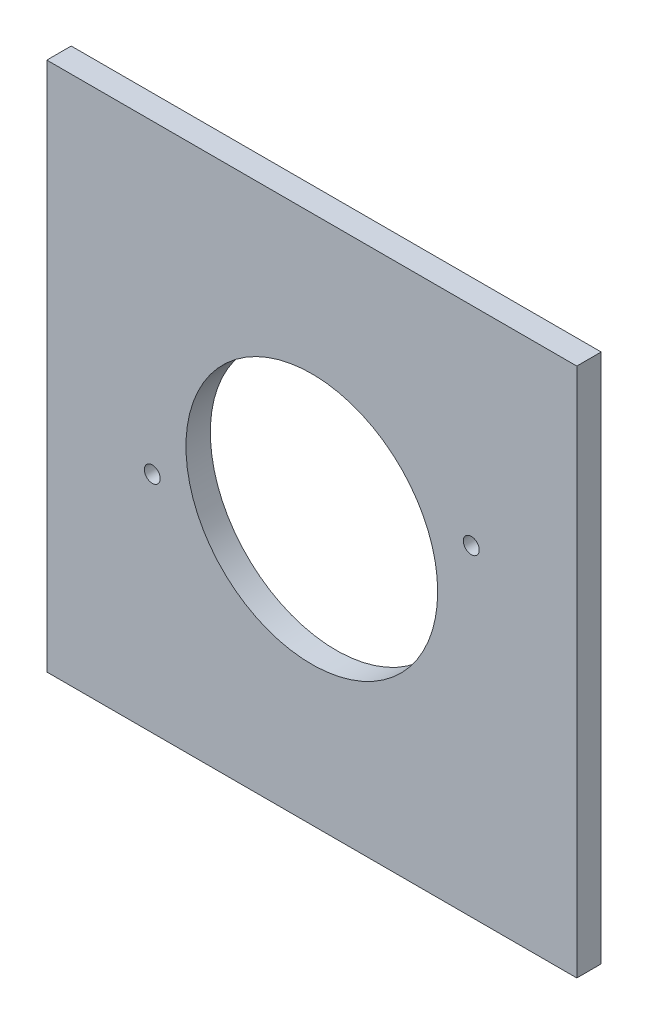
SolidWorks part; units mm, degrees
ref_plane "Plan de face" through (0, 0, 0) normal (0, 0, 1) x (1, 0, 0)
ref_plane "Plan de dessus" through (0, 0, 0) normal (0, 1, 0) x (1, 0, 0)
ref_plane "Plan de droite" through (0, 0, 0) normal (1, 0, 0) x (0, 0, -1)
sketch "Esquisse1" plane through (0, 0, 0) normal (0, 0, 1) x (1, 0, 0)
  line L1 (-44.1717, 36.1501) -> (55.8283, 36.1501)
  line L2 (-44.1717, 36.1501) -> (-44.1717, -13.8499)
  line L3 (-44.1717, -13.8499) -> (55.8283, -13.8499)
  line L4 (55.8283, 36.1501) -> (55.8283, -13.8499)
  line L6 (-44.1717, -13.8499) -> (55.8283, -13.8499)
  line L7 (-44.1717, -13.8499) -> (-44.1717, -63.8499)
  line L8 (-44.1717, -63.8499) -> (55.8283, -63.8499)
  line L9 (55.8283, -13.8499) -> (55.8283, -63.8499)
  arc A0 (29.5783, -13.8499) -> (-17.9217, -13.8499) centre (5.8283, -13.8499) ccw
  circle A1 centre (5.8283, -13.8499) radius 23.75
  dimension "D1" = 47.5
  dimension "D2" = 100
  dimension "D3" = 50
  dimension "D4" = 50
extrude "Boss.-Extru.1" add sketch "Esquisse1" along normal blind 4.6 contours A0 L3 L4 L1 L2 | A1 L3 L7 L8 L9
sketch "Esquisse2" plane through (0, 0, 4.6) normal (0, 0, 1) x (1, 0, 0)
  line L0 (-44.1717, -63.8499) -> (55.8283, -63.8499) construction
  line L1 (55.8283, 36.1501) -> (55.8283, -63.8499) construction
  line L2 (-44.1717, 36.1501) -> (-44.1717, -63.8499) construction
  circle A0 centre (-24.2717, -21.5599) radius 1.5
  circle A1 centre (35.9183, -3.1299) radius 1.5
  dimension "D1" = 3
  dimension "D2" = 3
  dimension "D5" = 60.72
  dimension "D6" = 42.29
  dimension "D3" = 19.91
  dimension "D4" = 19.9
extrude "Enlèv. mat.-Extru.1" cut sketch "Esquisse2" against normal blind 10
sketch "Esquisse3" plane through (0, 0, 0) normal (0, 0, -1) x (-1, 0, 0)
  circle A0 centre (-35.9183, -3.1299) radius 3
  circle A1 centre (24.2717, -21.5599) radius 3
  dimension "D1" = 6
  dimension "D2" = 6
extrude "Enlèv. mat.-Extru.2" cut sketch "Esquisse3" against normal blind 2
